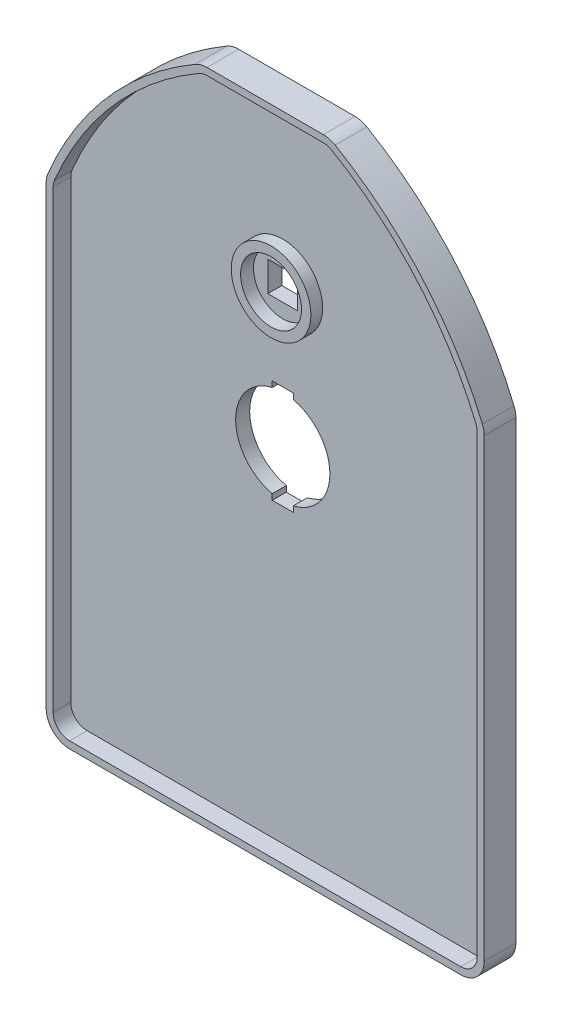
SolidWorks part; units mm, degrees
ref_plane "Front Plane" through (0, 0, 0) normal (0, 0, 1) x (1, 0, 0)
ref_plane "Top Plane" through (0, 0, 0) normal (0, 1, 0) x (1, 0, 0)
ref_plane "Right Plane" through (0, 0, 0) normal (1, 0, 0) x (0, 0, -1)
sketch "Sketch1" plane through (0, 0, 0) normal (0, 0, 1) x (1, 0, 0)
  line L12 (37.4, -55.9) -> (37.4, 21.8224)
  line L13 (9.9388, 52.61) -> (-9.9388, 52.61)
  line L14 (-37.4, 21.8224) -> (-37.4, -55.9)
  line L15 (-33.4, -59.9) -> (33.4, -59.9)
  line L20 (37.4, -55.9) -> (37.4, 21.8224)
  line L21 (9.9388, 52.61) -> (-9.9388, 52.61)
  line L22 (-37.4, 21.8224) -> (-37.4, -55.9)
  line L23 (-33.4, -59.9) -> (33.4, -59.9)
  arc A6 (37.0908, 23.3644) -> (11.9539, 52.0654) centre (-18.2718, 0.2348) ccw
  arc A7 (-11.9539, 52.0654) -> (-37.0908, 23.3644) centre (18.2718, 0.2348) ccw
  arc A10 (37.0908, 23.3644) -> (11.9539, 52.0654) centre (-18.2718, 0.2348) ccw
  arc A11 (-11.9539, 52.0654) -> (-37.0908, 23.3644) centre (18.2718, 0.2348) ccw
  arc A52 (33.4, -59.9) -> (37.4, -55.9) centre (33.4, -55.9) ccw
  arc A53 (33.4, -59.9) -> (37.4, -55.9) centre (33.4, -55.9) ccw
  arc A54 (37.4, 21.8224) -> (37.0908, 23.3644) centre (33.4, 21.8224) ccw
  arc A55 (37.4, 21.8224) -> (37.0908, 23.3644) centre (33.4, 21.8224) ccw
  arc A56 (11.9539, 52.0654) -> (9.9388, 52.61) centre (9.9388, 48.61) ccw
  arc A57 (11.9539, 52.0654) -> (9.9388, 52.61) centre (9.9388, 48.61) ccw
  arc A58 (-9.9388, 52.61) -> (-11.9539, 52.0654) centre (-9.9388, 48.61) ccw
  arc A59 (-9.9388, 52.61) -> (-11.9539, 52.0654) centre (-9.9388, 48.61) ccw
  arc A60 (-37.0908, 23.3644) -> (-37.4, 21.8224) centre (-33.4, 21.8224) ccw
  arc A61 (-37.0908, 23.3644) -> (-37.4, 21.8224) centre (-33.4, 21.8224) ccw
  arc A62 (-37.4, -55.9) -> (-33.4, -59.9) centre (-33.4, -55.9) ccw
  arc A63 (-37.4, -55.9) -> (-33.4, -59.9) centre (-33.4, -55.9) ccw
  dimension "D1" = 0
extrude "Boss-Extrude1" add sketch "Sketch1" along normal blind 2.4
sketch "Sketch2" plane through (0, 0, 2.4) normal (0, 0, 1) x (1, 0, 0)
  line L4 (-33.4, -59.9) -> (33.4, -59.9)
  line L6 (-33.4, -59.9) -> (33.4, -59.9)
  line L12 (37.4, -55.9) -> (37.4, 21.8224)
  line L14 (37.4, -55.9) -> (37.4, 21.8224)
  line L16 (9.9388, 52.61) -> (-9.9388, 52.61)
  line L17 (9.9388, 52.61) -> (-9.9388, 52.61)
  line L18 (-37.4, 21.8224) -> (-37.4, -55.9)
  line L19 (-37.4, 21.8224) -> (-37.4, -55.9)
  arc A2 (37.0908, 23.3644) -> (11.9539, 52.0654) centre (-18.2718, 0.2348) ccw
  arc A6 (37.0908, 23.3644) -> (11.9539, 52.0654) centre (-18.2718, 0.2348) ccw
  arc A8 (-11.9539, 52.0654) -> (-37.0908, 23.3644) centre (18.2718, 0.2348) ccw
  arc A9 (-11.9539, 52.0654) -> (-37.0908, 23.3644) centre (18.2718, 0.2348) ccw
  arc A16 (37.4, 21.8224) -> (37.0908, 23.3644) centre (33.4, 21.8224) ccw
  arc A17 (37.4, 21.8224) -> (37.0908, 23.3644) centre (33.4, 21.8224) ccw
  arc A18 (11.9539, 52.0654) -> (9.9388, 52.61) centre (9.9388, 48.61) ccw
  arc A19 (11.9539, 52.0654) -> (9.9388, 52.61) centre (9.9388, 48.61) ccw
  arc A20 (-9.9388, 52.61) -> (-11.9539, 52.0654) centre (-9.9388, 48.61) ccw
  arc A21 (-9.9388, 52.61) -> (-11.9539, 52.0654) centre (-9.9388, 48.61) ccw
  arc A22 (-37.0908, 23.3644) -> (-37.4, 21.8224) centre (-33.4, 21.8224) ccw
  arc A23 (-37.0908, 23.3644) -> (-37.4, 21.8224) centre (-33.4, 21.8224) ccw
  arc A24 (-37.4, -55.9) -> (-33.4, -59.9) centre (-33.4, -55.9) ccw
  arc A25 (-37.4, -55.9) -> (-33.4, -59.9) centre (-33.4, -55.9) ccw
  arc A26 (33.4, -59.9) -> (37.4, -55.9) centre (33.4, -55.9) ccw
  arc A27 (33.4, -59.9) -> (37.4, -55.9) centre (33.4, -55.9) ccw
  dimension "D1" = 0
extrude "Extrude-Thin1" add sketch "Sketch2" along normal blind 3 thin thin type one direction reverse wall 1.2
sketch "Sketch3" plane through (0, 0, 2.4) normal (0, 0, 1) x (1, 0, 0)
  line L0 (0, 13.1441) -> (0, -14.793) construction
  line L1 (-12.3992, 0) -> (16.9402, 0) construction
  line L2 (-1.8, 8.8224) -> (1.8, 8.8224)
  line L3 (-1.8, 10.1448) -> (-1.8, 7.5) construction
  line L4 (1.8, 10.1448) -> (1.8, 7.5) construction
  line L5 (1.8, 8.8224) -> (1.8, 7.8462)
  line L6 (-1.8, 8.8224) -> (-1.8, 7.8462)
  line L7 (-1.8, -8.8224) -> (-1.8, -7.8462)
  line L8 (1.8, -8.8224) -> (1.8, -7.8462)
  line L9 (-1.8, -8.8224) -> (1.8, -8.8224)
  circle A0 centre (0, 0) radius 8.05
  dimension "D1" = 16.1
extrude "Cut-Extrude1" cut sketch "Sketch3" against normal through all contours A0 L5 L2 L6 | A0 L7 L9 L8 | A0
sketch "Sketch4" plane through (0, 0, 2.4) normal (0, 0, 1) x (1, 0, 0)
  circle A0 centre (0, 23.9) radius 5
  circle A1 centre (0, 23.9) radius 5.2
  dimension "D1" = 0.2
extrude "Cut-Extrude2" cut sketch "Sketch4" against normal blind 0.8
sketch "Sketch5" plane through (0, 0, 0) normal (0, 0, -1) x (-1, 0, 0)
  line L0 (-2.55, 21.35) -> (-2.55, 26.45)
  line L1 (-2.4, 21.5) -> (2.4, 21.5)
  line L2 (-2.4, 21.5) -> (-2.4, 26.3)
  line L3 (-2.4, 26.3) -> (2.4, 26.3)
  line L4 (2.4, 21.5) -> (2.4, 26.3)
  line L5 (-2.55, 26.45) -> (2.55, 26.45)
  line L6 (2.55, 21.35) -> (2.55, 26.45)
  line L7 (-2.55, 21.35) -> (2.55, 21.35)
  dimension "D1" = 0.15
extrude "Cut-Extrude5" cut sketch "Sketch5" against normal through all contours L1 L4 L3 L2 | L0 L7 L6 L5 L4 L1 L2 L3
sketch "Sketch8" plane through (0, 0, 2.4) normal (0, 0, 1) x (1, 0, 0)
  circle A0 centre (0, 23.9) radius 5.2 construction
  circle A1 centre (0, 23.9) radius 5.2
  circle A2 centre (0, 23.9) radius 6.8
  dimension "D1" = 1.6
extrude "Boss-Extrude2" add sketch "Sketch8" along normal blind 2
equation "\"D1@Boss-Extrude1\"=\"Wall thickness@Box_Admin.Assembly\""
equation "\"D1\"= \"Groove length@Box_Admin.Assembly\""
equation "\"D5@Extrude-Thin1\"=\"Groove thickness@Box_Admin.Assembly\""
equation "\"D1@Sketch4\"=0.2"
